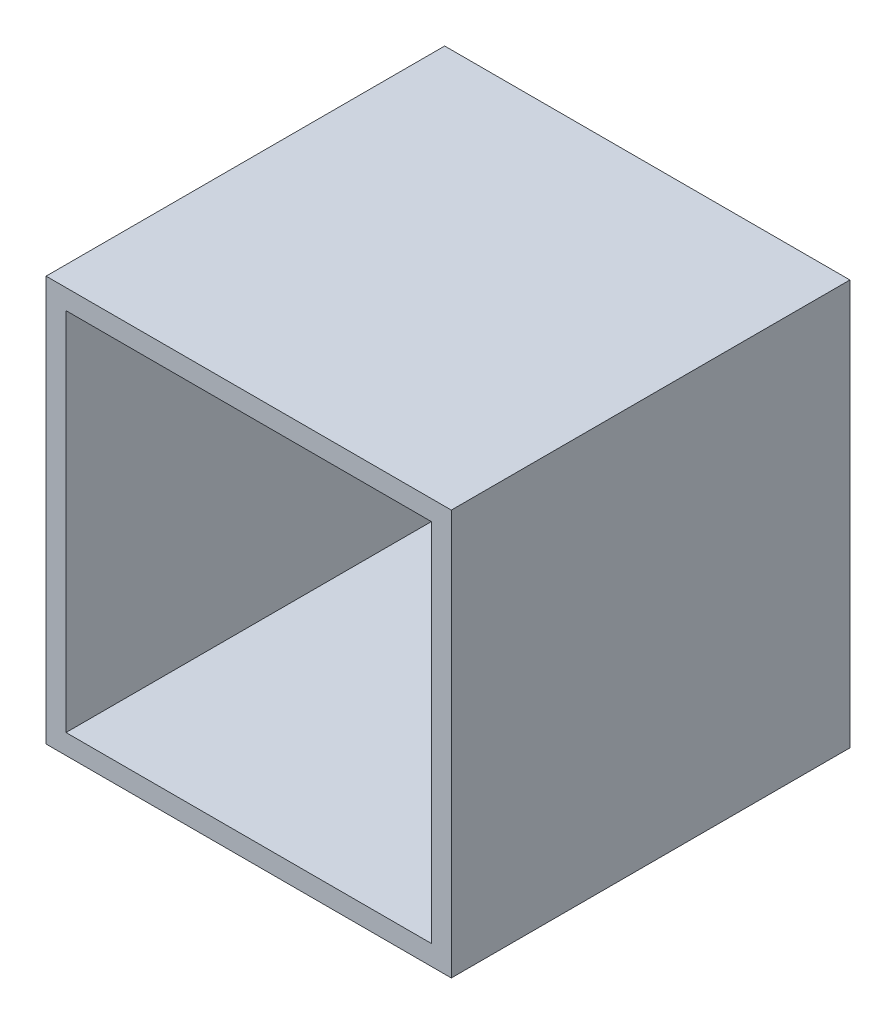
SolidWorks part; units mm, degrees
ref_plane "Front Plane" through (0, 0, 0) normal (0, 0, 1) x (1, 0, 0)
ref_plane "Top Plane" through (0, 0, 0) normal (0, 1, 0) x (1, 0, 0)
ref_plane "Right Plane" through (0, 0, 0) normal (1, 0, 0) x (0, 0, -1)
sketch "Sketch1" plane through (0, 0, 0) normal (0, 0, 1) x (1, 0, 0)
  line L0 (-30.5, -30.5) -> (-30.5, 30.5)
  line L1 (-27.5, -27.5) -> (27.5, -27.5)
  line L2 (-27.5, -27.5) -> (-27.5, 27.5)
  line L3 (-27.5, 27.5) -> (27.5, 27.5)
  line L4 (27.5, -27.5) -> (27.5, 27.5)
  line L5 (-27.5, -27.5) -> (27.5, 27.5) construction
  line L6 (-27.5, 27.5) -> (27.5, -27.5) construction
  line L7 (-30.5, 30.5) -> (30.5, 30.5)
  line L8 (30.5, -30.5) -> (30.5, 30.5)
  line L9 (-30.5, -30.5) -> (30.5, -30.5)
  point P0 (0, 0)
  dimension "D1" = 55
  dimension "D2" = 55
  dimension "D3" = 3
extrude "Boss-Extrude1" add sketch "Sketch1" along normal blind 60
sketch "Sketch2" plane through (0, 0, 0) normal (0, 0, -1) x (-1, 0, 0)
  line L4 (-30.5, -30.5) -> (30.5, -30.5)
  line L5 (30.5, -30.5) -> (30.5, 30.5)
  line L6 (30.5, 30.5) -> (-30.5, 30.5)
  line L7 (-30.5, 30.5) -> (-30.5, -30.5)
  line L8 (-30.5, -30.5) -> (30.5, -30.5)
  line L9 (30.5, -30.5) -> (30.5, 30.5)
  line L10 (30.5, 30.5) -> (-30.5, 30.5)
  line L11 (-30.5, 30.5) -> (-30.5, -30.5)
  dimension "D1" = 0
extrude "Boss-Extrude2" add sketch "Sketch2" against normal blind 3
sketch "Sketch3" plane through (0, 0, 0) normal (0, 0, -1) x (-1, 0, 0)
  line L1 (-14, -11) -> (14, -11)
  line L2 (-14, -11) -> (-14, 11)
  line L3 (-14, 11) -> (14, 11)
  line L4 (14, -11) -> (14, 11)
  line L5 (-14, -11) -> (14, 11) construction
  line L6 (-14, 11) -> (14, -11) construction
  circle A0 centre (-14, 11) radius 1.5
  circle A1 centre (-14, -11) radius 1.5
  circle A2 centre (14, 11) radius 1.5
  circle A3 centre (14, -11) radius 1.5
  point P0 (0, 0)
  dimension "D3" = 3
  dimension "D1" = 28
  dimension "D2" = 22
extrude "Cut-Extrude1" cut sketch "Sketch3" against normal blind 3 contours L1 A3 L4 | L4 A3 L1 | L2 A1 L1 | L1 A1 L2 | L4 A2 L3 | L3 A2 L4 | L2 A0 L3 | L3 A0 L2
sketch "Sketch4" plane through (0, 30.5, 0) normal (0, 1, 0) x (1, 0, 0)
  line L0 (27.5, -3) -> (-27.5, -3)
  line L1 (-27.5, -3) -> (-27.5, -60)
  line L2 (-27.5, -57) -> (27.5, -57)
  line L3 (27.5, -60) -> (27.5, -3)
  line L4 (30.5, 0) -> (-30.5, 0)
  line L5 (-30.5, 0) -> (-30.5, -60)
  line L6 (-30.5, -60) -> (30.5, -60)
  line L7 (30.5, -60) -> (30.5, 0)
  line L8 (30.5, 0) -> (-30.5, 0)
  line L9 (-30.5, 0) -> (-30.5, -60)
  line L10 (-30.5, -60) -> (30.5, -60)
  line L11 (30.5, -60) -> (30.5, 0)
  line L12 (-30.5, -20) -> (-30.5, -30)
  line L13 (-30.5, 0) -> (-27.5, 0)
  line L14 (-30.5, 0) -> (-30.5, -10)
  line L15 (-30.5, -10) -> (-27.5, -10)
  line L16 (-27.5, 0) -> (-27.5, -10)
  line L17 (-30.5, -20) -> (-27.5, -20)
  line L18 (-27.5, -20) -> (-27.5, -30)
  line L19 (-30.5, -30) -> (-27.5, -30)
  line L20 (-30.5, -40) -> (-30.5, -50)
  line L21 (-30.5, -40) -> (-27.5, -40)
  line L22 (-27.5, -40) -> (-27.5, -50)
  line L23 (-30.5, -50) -> (-27.5, -50)
  line L24 (0, 0) -> (0, -60)
  line L25 (11.5, -3) -> (3.5, -3)
  line L26 (-30.5, 0) -> (-19.5, 0)
  line L27 (-30.5, 0) -> (-30.5, -3)
  line L28 (-30.5, -3) -> (-19.5, -3)
  line L29 (-19.5, 0) -> (-19.5, -3)
  line L30 (30.5, 0) -> (19.5, 0)
  line L31 (30.5, 0) -> (30.5, -3)
  line L32 (30.5, -3) -> (19.5, -3)
  line L33 (19.5, 0) -> (19.5, -3)
  line L34 (-11.5, 0) -> (-3.5, 0)
  line L35 (-11.5, 0) -> (-11.5, -3)
  line L36 (-11.5, -3) -> (-3.5, -3)
  line L37 (-3.5, 0) -> (-3.5, -3)
  line L38 (3.5, 0) -> (3.5, -3)
  line L39 (11.5, 0) -> (3.5, 0)
  line L40 (11.5, 0) -> (11.5, -3)
  line L41 (30.5, -40) -> (27.5, -40)
  line L42 (27.5, -40) -> (27.5, -50)
  line L43 (30.5, -50) -> (27.5, -50)
  line L44 (30.5, -40) -> (30.5, -50)
  line L45 (30.5, -20) -> (27.5, -20)
  line L46 (27.5, -20) -> (27.5, -30)
  line L47 (30.5, -30) -> (27.5, -30)
  line L48 (30.5, -20) -> (30.5, -30)
  line L49 (30.5, -10) -> (27.5, -10)
  line L50 (27.5, 0) -> (27.5, -10)
  line L51 (30.5, 0) -> (27.5, 0)
  line L52 (30.5, 0) -> (30.5, -10)
  line L53 (-27.5, -3) -> (-27.5, -57) construction
  line L54 (27.5, -57) -> (27.5, -3) construction
  dimension "D3" = 10
  dimension "D5" = 11
  dimension "D6" = 11
  dimension "D7" = 8
  dimension "D8" = 8
  dimension "D1" = 0
  dimension "D2" = 3
  dimension "D4" = 3
